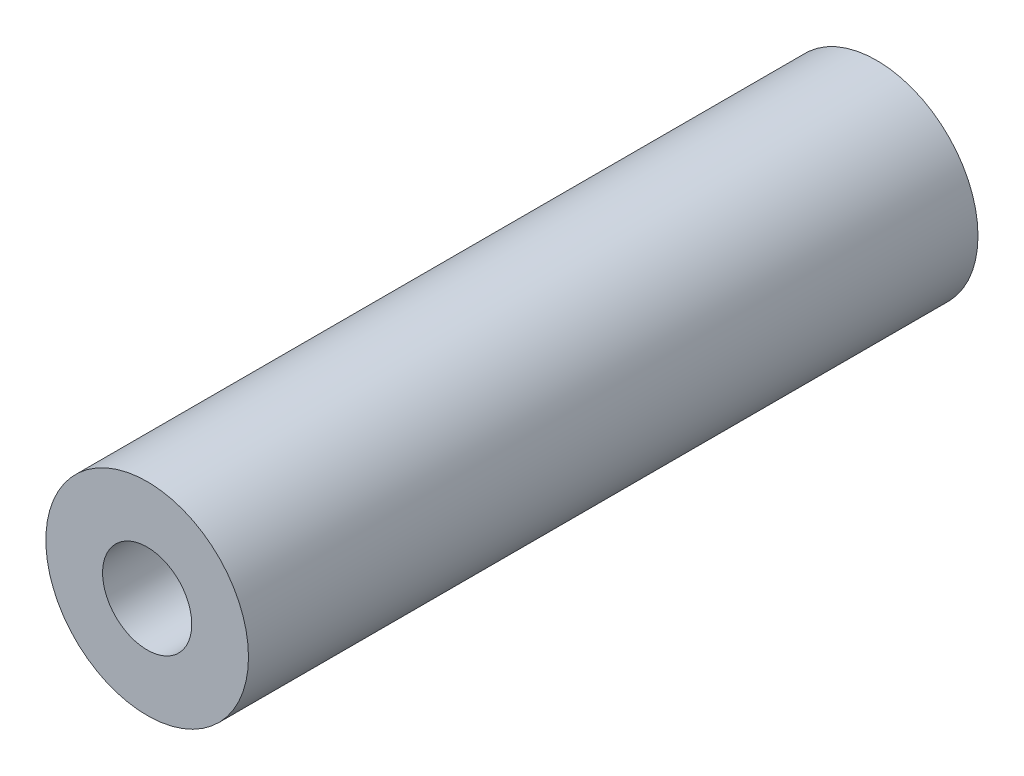
SolidWorks part; units mm, degrees
ref_plane "Front" through (0, 0, 0) normal (0, 0, 1) x (1, 0, 0)
ref_plane "Top" through (0, 0, 0) normal (0, 1, 0) x (1, 0, 0)
ref_plane "Right" through (0, 0, 0) normal (1, 0, 0) x (0, 0, -1)
sketch "Sketch1" plane through (0, 0, 0) normal (0, 0, 1) x (1, 0, 0)
  circle A0 centre (0, 0) radius 3.75
  dimension "D1" = 7.5
extrude "Boss-Extrude1" add sketch "Sketch1" along normal blind 27
hole_wizard "M4 Tapped Hole1" positions "Sketch2" profile "Sketch4" tap size "M4" standard "ISO"
sketch "Sketch2" plane through (0, 0, 27) normal (0, 0, 1) x (1, 0, 0)
  point P0 (0, 0)
sketch "Sketch4" plane through (0, 0, 27) normal (1, 0, 0) x (0, -1, 0)
  line L0 (0, 0) -> (0, 5.9914)
  line L1 (0, 5.9914) -> (1.65, 5)
  line L2 (1.65, 5) -> (1.65, 0)
  line L5 (1.65, 0) -> (0, 0)
  line L10 (0, 5.9914) -> (-1.65, 5) construction
  line L11 (0, -6.35) -> (0, 107.95) construction
  dimension "Tap Drill Dia." = 3.3
  dimension "Tap Drill Depth" = 5
  dimension "Drill Angle" = 118
cosmetic thread "Hole Thread2" parameters "D1"=5, "D2"=4
hole_wizard "M4 Tapped Hole2" positions "Sketch5" profile "Sketch6" tap size "M4" standard "ISO"
sketch "Sketch5" plane through (0, 0, 0) normal (0, 0, -1) x (-1, 0, 0)
  point P0 (0, 0)
sketch "Sketch6" plane through (0, 0, 0) normal (1, 0, 0) x (0, 1, 0)
  line L0 (0, 0) -> (0, 8.0914)
  line L1 (0, 8.0914) -> (1.65, 7.1)
  line L2 (1.65, 7.1) -> (1.65, 0)
  line L5 (1.65, 0) -> (0, 0)
  line L10 (0, 8.0914) -> (-1.65, 7.1) construction
  line L11 (0, -6.35) -> (0, 107.95) construction
  dimension "Tap Drill Dia." = 3.3
  dimension "Tap Drill Depth" = 7.1
  dimension "Drill Angle" = 118
cosmetic thread "Hole Thread3" parameters "D1"=5, "D2"=4
scale "Scale1" scale about centroid uniform scaling yes scale factor 1.013
